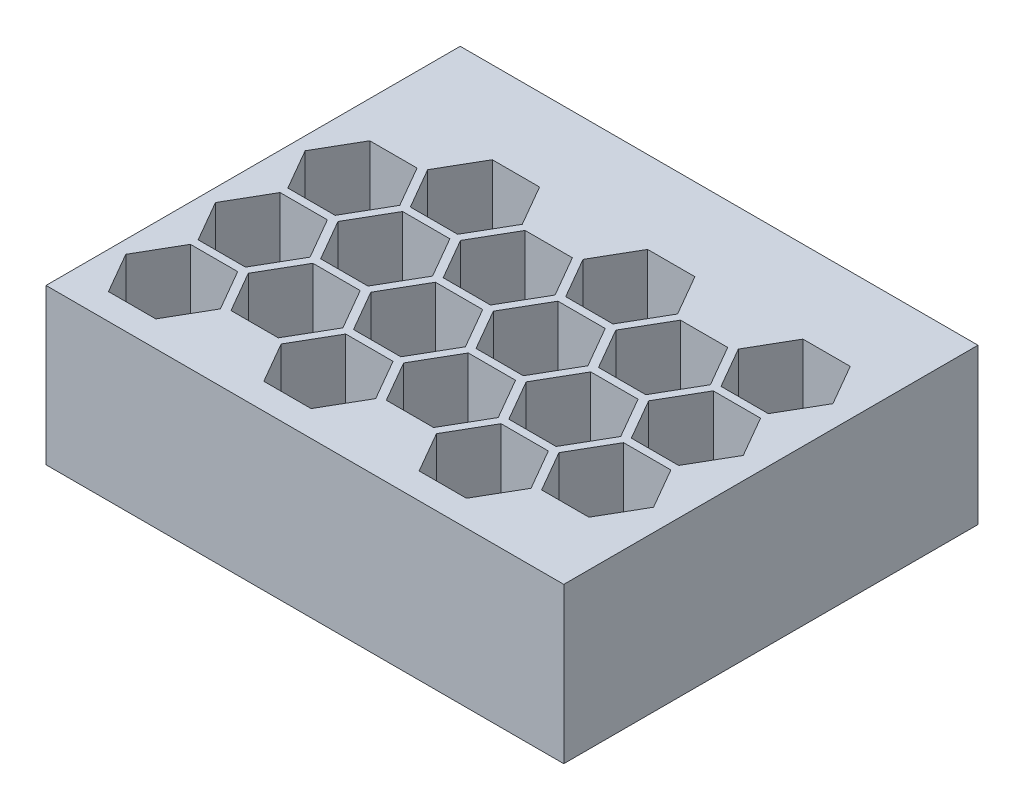
SolidWorks part; units mm, degrees
material "AISI 1020"
ref_plane "Front Plane" through (0, 0, 0) normal (0, 0, 1) x (1, 0, 0)
ref_plane "Top Plane" through (0, 0, 0) normal (0, 1, 0) x (1, 0, 0)
ref_plane "Right Plane" through (0, 0, 0) normal (1, 0, 0) x (0, 0, -1)
sketch "Sketch1" plane through (0, 0, 0) normal (0, 1, 0) x (1, 0, 0)
  line L1 (0, 0) -> (10, 0)
  line L2 (0, 0) -> (0, 8)
  line L3 (0, 8) -> (10, 8)
  line L4 (10, 0) -> (10, 8)
  dimension "D1" = 10
  dimension "D2" = 8
extrude "Boss-Extrude1" add sketch "Sketch1" along normal blind 3
sketch "Sketch2" plane through (0, 3, 0) normal (0, 1, 0) x (1, 0, 0)
  line L0 (1.1634, 1.291) -> (2.6634, 2.1571) construction
  line L1 (2.0768, 1.291) -> (1.6201, 2.0821)
  line L2 (1.6201, 2.0821) -> (0.7067, 2.0821)
  line L3 (0.7067, 2.0821) -> (0.25, 1.291)
  line L4 (0.25, 1.291) -> (0.7067, 0.5)
  line L5 (0.7067, 0.5) -> (1.6201, 0.5)
  line L6 (1.6201, 0.5) -> (2.0768, 1.291)
  line L7 (3.5768, 2.1571) -> (3.1201, 2.9481)
  line L8 (3.1201, 2.9481) -> (2.2067, 2.9481)
  line L9 (2.2067, 2.9481) -> (1.75, 2.1571)
  line L10 (1.75, 2.1571) -> (2.2067, 1.366)
  line L11 (2.2067, 1.366) -> (3.1201, 1.366)
  line L12 (3.1201, 1.366) -> (3.5768, 2.1571)
  line L13 (0, 0) -> (10, 0) construction
  line L14 (0, 8) -> (0, 0) construction
  line L15 (2.6634, 2.1571) -> (4.1634, 1.291) construction
  line L16 (4.1634, 1.291) -> (1.1634, 1.291) construction
  line L17 (1.1634, 2.0821) -> (1.1634, 2.2321) construction
  line L18 (1.1634, 2.2321) -> (1.1634, 3.0231) construction
  line L19 (1.1634, 2.0821) -> (1.1634, 1.291) construction
  line L20 (2.0768, 1.291) -> (2.2067, 1.366) construction
  circle A0 centre (1.1634, 1.291) radius 0.791 construction
  circle A1 centre (2.6634, 2.1571) radius 0.791 construction
  dimension "D1" = 0.5
  dimension "D2" = 0.25
  dimension "D3" = 0.15
  dimension "D4" = 30
  dimension "D5" = 3
  dimension "D6" = 1.7321
extrude "Cut-Extrude1" cut sketch "Sketch2" against normal up to next
pattern_linear "LPattern2" count 3 spacing 3 along (1, 0, 0) count 3 spacing 1.7321 along (0, 0, -1) of "Cut-Extrude1"
equation "\"D3@LPattern1\"=\"D5@Sketch2\""
equation "\"D4@LPattern1\"=\"D6@Sketch2\""
equation "\"D3@LPattern2\"=\"D5@Sketch2\""
equation "\"D4@LPattern2\"=\"D6@Sketch2\""
